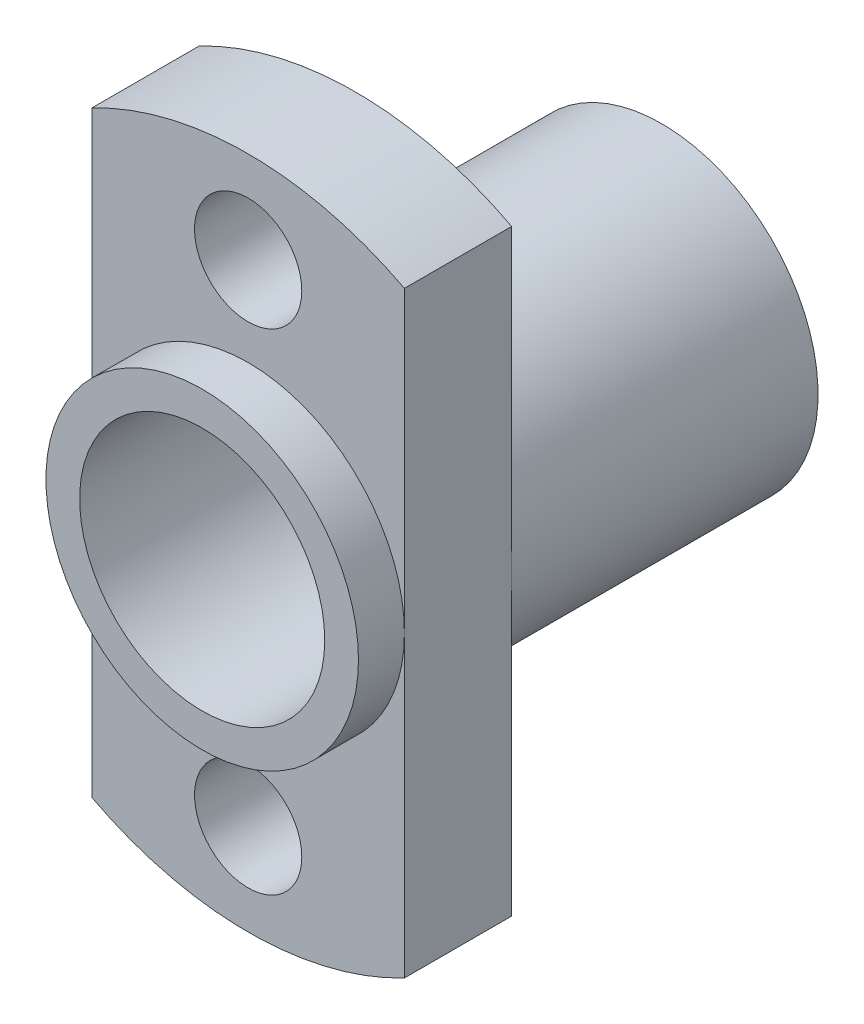
SolidWorks part; units mm, degrees
ref_plane "前视基准面" through (0, 0, 0) normal (0, 0, 1) x (1, 0, 0)
ref_plane "上视基准面" through (0, 0, 0) normal (0, 1, 0) x (1, 0, 0)
ref_plane "右视基准面" through (0, 0, 0) normal (1, 0, 0) x (0, 0, -1)
other "Configuration Table"
sketch "草图1" plane through (0, 0, 0) normal (0, 0, 1) x (1, 0, 0)
  circle A0 centre (0, 0) radius 11
  dimension "D1" = 22
extrude "凸台-拉伸1" add sketch "草图1" along normal blind 3.5
sketch "草图2" plane through (0, 0, 3.5) normal (0, 0, 1) x (1, 0, 0)
  line L2 (-5.1, -9.7463) -> (-5.1, 9.7463)
  line L4 (5.1, -9.7463) -> (5.1, 9.7463)
  line L5 (-4.5167, -10.0299) -> (4.5167, 10.0299) construction
  line L6 (-4.5167, 10.0299) -> (4.5167, -10.0299) construction
  circle A1 centre (0, 0) radius 11
  circle A2 centre (0, 0) radius 11
  point P0 (0, 0)
  circle M6 centre (0, 0) radius 11
  dimension "D1" = 0
extrude "切除-拉伸1" cut sketch "草图2" against normal up to next contours L2 M6 | L4 M6
sketch "草图3" plane through (0, 0, 3.5) normal (0, 0, 1) x (1, 0, 0)
  circle A0 centre (0, 0) radius 5.1
  dimension "D1" = 10.2
extrude "凸台-拉伸2" add sketch "草图3" along normal blind 1.5
sketch "草图4" plane through (0, 0, 0) normal (0, 0, -1) x (-1, 0, 0)
  circle A0 centre (0, 0) radius 5.1
  dimension "D1" = 10.2
extrude "凸台-拉伸3" add sketch "草图4" along normal blind 10
sketch "草图5" plane through (0, 0, 3.5) normal (0, 0, 1) x (1, 0, 0)
  circle A0 centre (0, 0) radius 8 construction
  circle A1 centre (0, 8) radius 1.75
  circle A2 centre (0, -8) radius 1.75
  dimension "D1" = 16
  dimension "D2" = 3.5
  dimension "D3" = 3.5
extrude "切除-拉伸2" cut sketch "草图5" against normal up to next
sketch "草图6" plane through (0, 0, 5) normal (0, 0, 1) x (1, 0, 0)
  circle A0 centre (0, 0) radius 4
  dimension "D1" = 8
extrude "切除-拉伸3" cut sketch "草图6" against normal up to next
